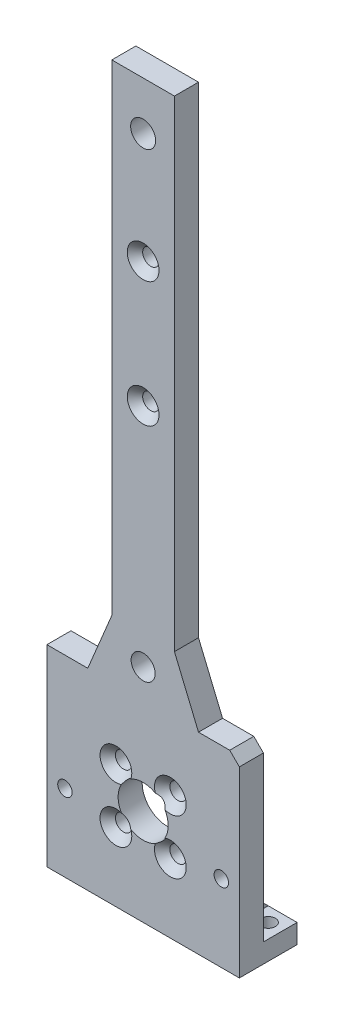
SolidWorks part; units mm, degrees
ref_plane "前视基准面" through (0, 0, 0) normal (0, 0, 1) x (1, 0, 0)
ref_plane "上视基准面" through (0, 0, 0) normal (0, 1, 0) x (1, 0, 0)
ref_plane "右视基准面" through (0, 0, 0) normal (1, 0, 0) x (0, 0, -1)
other "Configuration Table"
sketch "草图1" plane through (0, 0, 0) normal (0, 0, 1) x (1, 0, 0)
  line L0 (-20, 0) -> (20, 0) construction
  line L1 (-20, -20) -> (20, -20)
  line L2 (-20, -20) -> (-20, 20)
  line L3 (-20, 20) -> (20, 20)
  line L4 (20, -20) -> (20, 20)
  line L5 (-20, -20) -> (20, 20) construction
  line L6 (-20, 20) -> (20, -20) construction
  line L7 (0, 20) -> (0, -20) construction
  line L9 (-5.6569, -5.6569) -> (5.6569, -5.6569) construction
  line L10 (-5.6569, -5.6569) -> (-5.6569, 5.6569) construction
  line L11 (-5.6569, 5.6569) -> (5.6569, 5.6569) construction
  line L12 (5.6569, -5.6569) -> (5.6569, 5.6569) construction
  line L13 (-5.6569, -5.6569) -> (5.6569, 5.6569) construction
  line L14 (-5.6569, 5.6569) -> (5.6569, -5.6569) construction
  circle A2 centre (0, 0) radius 5.2
  circle A3 centre (0, 0) radius 8 construction
  circle A4 centre (5.6569, 5.6569) radius 1.6
  circle A5 centre (5.6569, -5.6569) radius 1.6
  circle A6 centre (-5.6569, -5.6569) radius 1.6
  circle A7 centre (-5.6569, 5.6569) radius 1.6
  point P0 (0, 0)
  point P31 (0, 0)
  dimension "D6" = 10.4
  dimension "D7" = 16
  dimension "D8" = 3.2
  dimension "D1" = 40
  dimension "D2" = 40
  dimension "D9" = 4
extrude "凸台-拉伸1" add sketch "草图1" along normal blind 5
hole_wizard "孔1" positions "3D草图1" profile "草图2" legacy end condition through all
sketch3d "3D草图1"
  line L0 (0, 20, 5) -> (0, -20, 5) construction
  line L1 (20, 20, 5) -> (-20, 20, 5) construction
  line L2 (-20, -20, 5) -> (20, -20, 5) construction
  line L3 (-20, 0, 5) -> (20, 0, 5) construction
  line L4 (-20, 20, 5) -> (-20, -20, 5) construction
  line L5 (20, -20, 5) -> (20, 20, 5) construction
  point P0 (16.25, -4, 5)
  point P2 (-16.25, -4, 5)
  dimension "D1" = 16.25
  dimension "D2" = 16.25
  dimension "D3" = 4
  dimension "D4" = 4
sketch "草图2" plane through (16.25, -4, 5) normal (1, 0, 0) x (0, -1, 0)
  line L0 (0, 0) -> (0, 5)
  line L1 (0, 5) -> (1.5, 5)
  line L2 (1.5, 5) -> (1.5, 0)
  line L3 (1.5, 0) -> (0, 0)
  line L4 (0, 110) -> (0, -10) construction
  dimension "直径" = 3
  dimension "深度" = 5
chamfer "倒角1" distance 2 angle 45 1 edges at (20, 20, 2.5)
hole_wizard "M3 十字槽沉头木螺钉的锥形沉头孔2" positions "草图5" profile "草图6" countersink size "M3" standard "GB" end condition through all
sketch "草图5" plane through (0, 0, 5) normal (0, 0, 1) x (1, 0, 0)
  point P0 (-5.6569, 5.6569)
  point P3 (5.6569, 5.6569)
  point P6 (5.6569, -5.6569)
  point P9 (-5.6569, -5.6569)
sketch "草图6" plane through (-5.6569, 5.6569, 5) normal (1, 0, 0) x (0, -1, 0)
  line L0 (0, 0) -> (0, 5)
  line L1 (0, 5) -> (1.7, 5)
  line L2 (1.7, 5) -> (1.7, 1.6)
  line L3 (1.7, 1.6) -> (3.3, 0)
  line L5 (3.3, 0) -> (0, 0)
  line L6 (-1.7, 1.6) -> (-3.3, 0) construction
  line L11 (0, -6.35) -> (0, 107.95) construction
  dimension "通孔孔直径" = 3.4
  dimension "通孔孔深度" = 5
  dimension "近端锥形沉头孔直径" = 6.6
  dimension "近端锥形沉头孔角度" = 90
sketch "草图7" plane through (0, 0, 0) normal (0, 0, -1) x (-1, 0, 0)
  line L0 (0, -20) -> (0, 33.662) construction
  line L1 (20, -20) -> (-20, -20) construction
  line L2 (-18, 20) -> (20, 20) construction
  line L3 (-6.5078, 20) -> (6.5078, 20)
  line L4 (-6.5078, 20) -> (-6.5078, 32) construction
  line L5 (-6.5078, 32) -> (6.5078, 32)
  line L6 (6.5078, 20) -> (6.5078, 32) construction
  line L7 (6.5078, 32) -> (11.5078, 20)
  line L8 (-6.5078, 32) -> (-11.5078, 20)
  line L9 (-6.5078, 26) -> (6.5078, 26) construction
  circle A1 centre (0, 26) radius 2.5
  line M11 (20, 20) -> (-18, 20)
  dimension "D4" = 5
  dimension "D1" = 5
  dimension "D2" = 5
  dimension "D3" = 12
extrude "凸台-拉伸2" add sketch "草图7" against normal up to surface (5 mm away) contours L5 L8 L7 A1 M11 up to face at (17.75, -4, 5)
sketch "草图10" plane through (0, -20, 0) normal (0, -1, 0) x (1, 0, 0)
  line L1 (20, 0) -> (11, 0)
  line L2 (20, 0) -> (20, -7)
  line L3 (20, -7) -> (11, -7)
  line L4 (11, 0) -> (11, -7)
  circle A0 centre (17, -4) radius 1.5
  dimension "D5" = 3
  dimension "D1" = 7
  dimension "D2" = 9
  dimension "D3" = 4
  dimension "D4" = 3
extrude "凸台-拉伸4" add sketch "草图10" against normal blind 4
ref_plane "基准面1" through (0, 0, 0) normal (1, 0, 0) x (0, 0, -1)
sketch "草图12" plane through (11, 0, 0) normal (-1, 0, 0) x (0, 0, 1)
  line L0 (-7, -16) -> (0, -9)
  line L1 (0, 20) -> (0, -20) construction
  line L2 (0, -9) -> (0, -16)
  line L3 (0, -16) -> (-7, -16)
  dimension "D1" = 45
extrude "凸台-拉伸6" add sketch "草图12" against normal blind 3
mirror "镜向2" about plane through (0, 0, 0) normal (1, 0, 0) of "凸台-拉伸4", "凸台-拉伸6"
sketch "草图13" plane through (0, 0, 5) normal (0, 0, 1) x (1, 0, 0)
  line L1 (-6.5078, 32) -> (6.5078, 32)
  line L2 (-6.5078, 32) -> (-6.5078, 132)
  line L3 (-6.5078, 132) -> (6.5078, 132)
  line L4 (6.5078, 32) -> (6.5078, 132)
  circle A0 centre (0, 122) radius 2.6
  circle A1 centre (0, 99) radius 1.5
  circle A2 centre (0, 73) radius 1.5
  dimension "D2" = 5.2
  dimension "D6" = 3
  dimension "D7" = 3
  dimension "D1" = 100
  dimension "D3" = 10
  dimension "D4" = 23
  dimension "D5" = 26
extrude "凸台-拉伸7" add sketch "草图13" against normal up to surface (5 mm away) up to face at (-3.9569, 5.6569, 0)
hole_wizard "M3 十字槽沉头木螺钉的锥形沉头孔3" positions "草图14" profile "草图15" countersink size "M3" standard "GB" end condition through all
sketch "草图14" plane through (0, 0, 5) normal (0, 0, 1) x (1, 0, 0)
  point P0 (0, 99)
  point P3 (0, 73)
sketch "草图15" plane through (0, 99, 5) normal (1, 0, 0) x (0, -1, 0)
  line L0 (0, 0) -> (0, 12)
  line L1 (0, 12) -> (1.7, 12)
  line L2 (1.7, 12) -> (1.7, 1.6)
  line L3 (1.7, 1.6) -> (3.3, 0)
  line L5 (3.3, 0) -> (0, 0)
  line L6 (-1.7, 1.6) -> (-3.3, 0) construction
  line L11 (0, -6.35) -> (0, 107.95) construction
  dimension "通孔孔直径" = 3.4
  dimension "通孔孔深度" = 12
  dimension "近端锥形沉头孔直径" = 6.6
  dimension "近端锥形沉头孔角度" = 90
